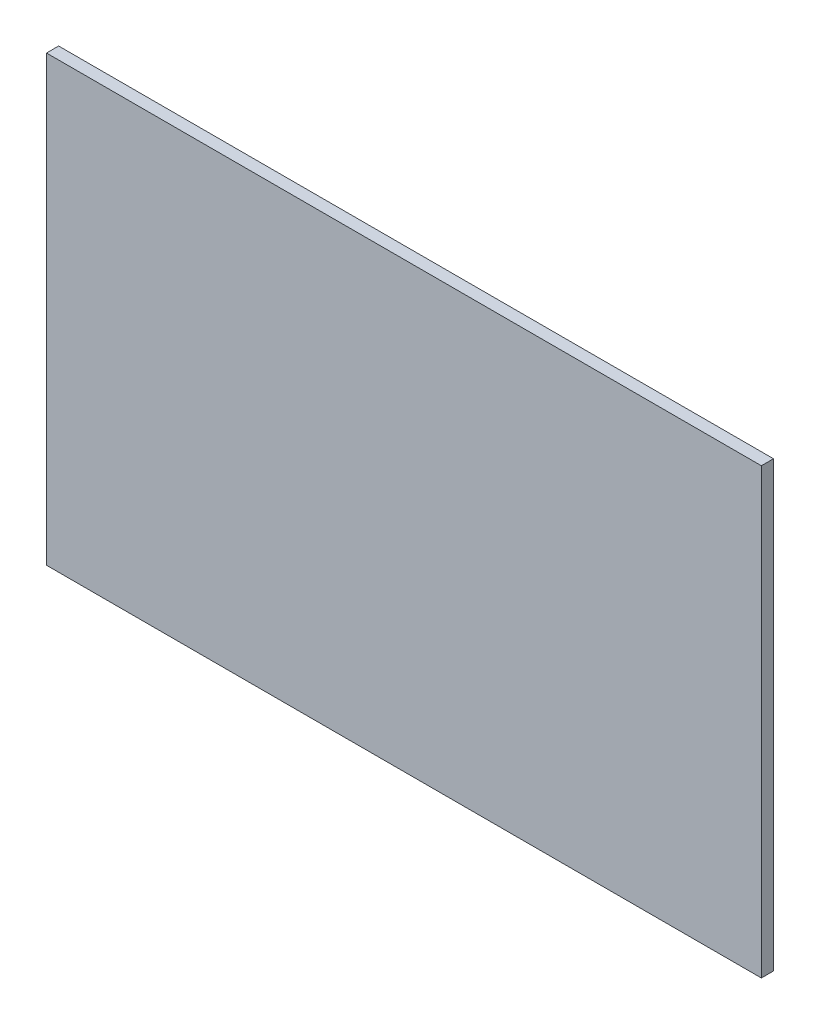
SolidWorks part; units mm, degrees
ref_plane "Plan de face" through (0, 0, 0) normal (0, 0, 1) x (1, 0, 0)
ref_plane "Plan de dessus" through (0, 0, 0) normal (0, 1, 0) x (1, 0, 0)
ref_plane "Plan de droite" through (0, 0, 0) normal (1, 0, 0) x (0, 0, -1)
sketch "Esquisse1" plane through (0, 0, 0) normal (0, 0, 1) x (1, 0, 0)
  line L1 (134.4972, -87.4812) -> (-159.9131, -87.4812)
  line L2 (134.4972, -87.4812) -> (134.4972, 95.2251)
  line L3 (134.4972, 95.2251) -> (-159.9131, 95.2251)
  line L4 (-159.9131, -87.4812) -> (-159.9131, 95.2251)
extrude "Boss.-Extru.1" add sketch "Esquisse1" along normal blind 5
